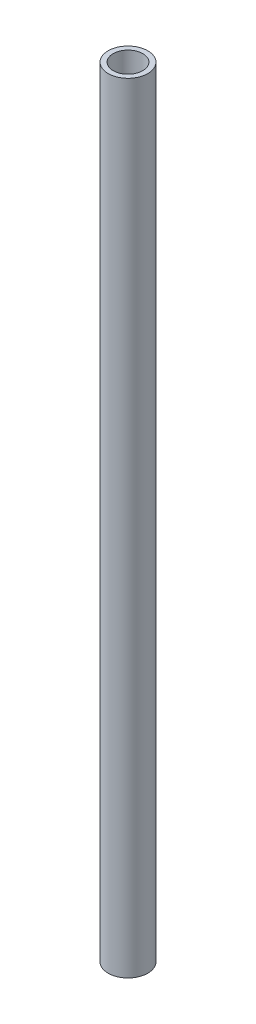
SolidWorks part; units mm, degrees
ref_plane "Front Plane" through (0, 0, 0) normal (0, 0, 1) x (1, 0, 0)
ref_plane "Top Plane" through (0, 0, 0) normal (0, 1, 0) x (1, 0, 0)
ref_plane "Right Plane" through (0, 0, 0) normal (1, 0, 0) x (0, 0, -1)
sketch "Sketch1" plane through (0, 0, 0) normal (0, 1, 0) x (1, 0, 0)
  circle A0 centre (0, 0) radius 9.5
  circle A1 centre (0, 0) radius 12.7
  dimension "D1" = 19
  dimension "D2" = 25.4
extrude "Boss-Extrude1" add sketch "Sketch1" along normal blind 500
